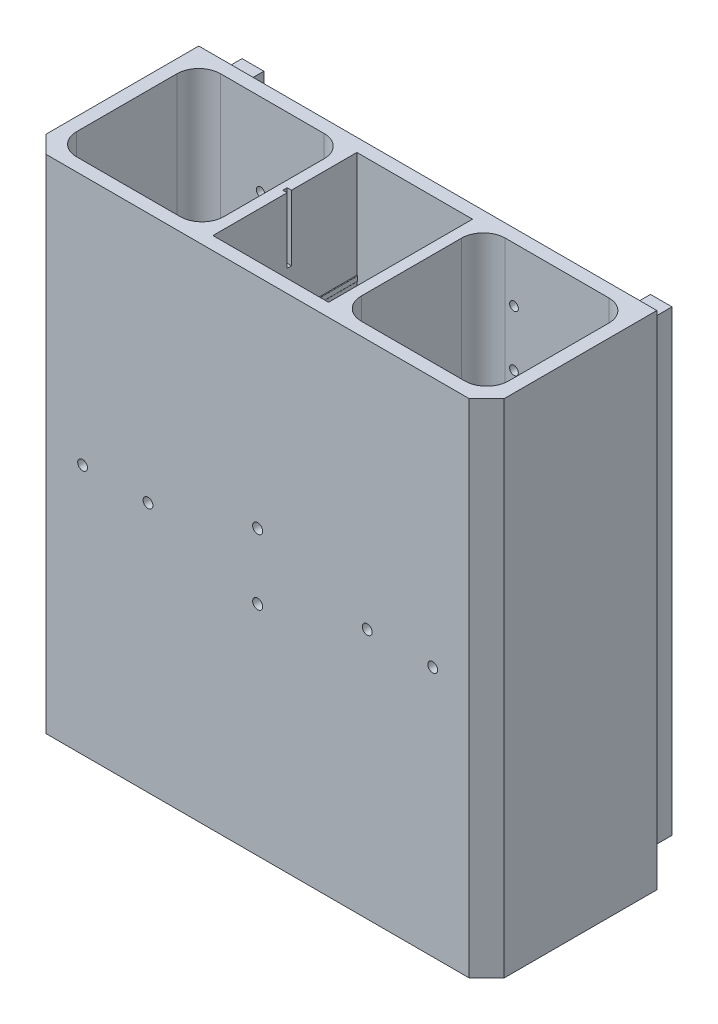
SolidWorks part; units mm, degrees
ref_plane "前视基准面" through (0, 0, 0) normal (0, 0, 1) x (1, 0, 0)
ref_plane "上视基准面" through (0, 0, 0) normal (0, 1, 0) x (1, 0, 0)
ref_plane "右视基准面" through (0, 0, 0) normal (1, 0, 0) x (0, 0, -1)
other "Configuration Table"
sketch "草图1" plane through (0, 0, 0) normal (0, 0, 1) x (1, 0, 0)
  line L1 (0, 0) -> (210, 0)
  line L2 (0, 0) -> (0, 230)
  line L3 (0, 230) -> (210, 230)
  line L4 (210, 0) -> (210, 230)
  line L5 (0, 0) -> (210, 230) construction
  line L6 (0, 230) -> (210, 0) construction
  line L7 (0, 230) -> (26, 230)
  line L8 (0, 230) -> (0, 0)
  line L9 (0, 0) -> (26, 0)
  point P4 (105, 115)
  point P8 (13, 115)
  dimension "D1" = 230
  dimension "D2" = 210
extrude "凸台-拉伸1" add sketch "草图1" along normal blind 6 contours L1 L4 L3 L2
sketch "草图2" plane through (0, 0, 0) normal (0, 0, -1) x (-1, 0, 0)
  line L0 (0, 230) -> (-210, 230) construction
  line L1 (0, 0) -> (-210, 0) construction
  line L2 (-210, 230) -> (-184, 230)
  line L3 (-210, 230) -> (-210, 0)
  line L4 (-210, 0) -> (-184, 0)
  line L5 (-184, 230) -> (-184, 0) construction
  line L6 (-210, 230) -> (-184, 0) construction
  line L7 (-210, 0) -> (-184, 230) construction
  line L9 (0, 230) -> (-20, 230)
  line L10 (0, 230) -> (0, 0)
  line L11 (0, 0) -> (-20, 0)
  line L13 (0, 230) -> (-20, 0) construction
  line L14 (0, 0) -> (-20, 230) construction
  line L15 (-201.925, 219.925) -> (-192.075, 219.925)
  line L16 (-201.925, 219.925) -> (-201.925, 10.075)
  line L17 (-201.925, 10.075) -> (-192.075, 10.075)
  line L18 (-192.075, 219.925) -> (-192.075, 10.075)
  line L19 (-201.925, 219.925) -> (-192.075, 10.075) construction
  line L20 (-201.925, 10.075) -> (-192.075, 219.925) construction
  line L21 (-14.85, 219.925) -> (-4.85, 219.925)
  line L22 (-14.85, 219.925) -> (-14.85, 10.075)
  line L23 (-14.85, 10.075) -> (-4.85, 10.075)
  line L24 (-4.85, 219.925) -> (-4.85, 10.075)
  line L25 (-14.85, 219.925) -> (-4.85, 10.075) construction
  line L26 (-14.85, 10.075) -> (-4.85, 219.925) construction
  point P6 (-197, 115)
  point P18 (-197, 115)
  point P23 (-9.85, 115)
  dimension "D1" = 26
  dimension "D2" = 20
  dimension "D3" = 209.85
  dimension "D4" = 9.85
  dimension "D5" = 13
  dimension "D6" = 115
  dimension "D7" = 209.85
  dimension "D8" = 115
  dimension "D9" = 9.85
  dimension "D10" = 10
extrude "凸台-拉伸3" add sketch "草图2" along normal blind 15 contours L18 L15 L16 L17 | L24 L21 L22 L23
sketch "草图3" plane through (0, 0, 0) normal (0, 0, -1) x (-1, 0, 0)
  line L0 (0, 0) -> (-210, 0) construction
  line L1 (-210, 230) -> (-184, 230)
  line L2 (-210, 230) -> (-210, 0)
  line L3 (-210, 0) -> (-184, 0)
  line L4 (-184, 230) -> (-184, 0)
  line L5 (-210, 230) -> (-184, 0) construction
  line L6 (-210, 0) -> (-184, 230) construction
  line L7 (-210, 115) -> (119.2636, 115) construction
  line L8 (0, 230) -> (-20, 230)
  line L9 (0, 230) -> (0, 0)
  line L10 (0, 0) -> (-20, 0)
  line L11 (-20, 230) -> (-20, 0)
  line L12 (0, 230) -> (-20, 0) construction
  line L13 (0, 0) -> (-20, 230) construction
  line L14 (-105, 230) -> (-105, 0) construction
  circle A0 centre (-169.6426, 192.25) radius 2
  circle A1 centre (-150.5, 205) radius 2
  circle A2 centre (-150.5, 179.5) radius 2
  circle A3 centre (-150.5, 50.5) radius 2
  circle A4 centre (-150.5, 25) radius 2
  circle A5 centre (-169.6426, 37.75) radius 2
  circle A6 centre (-34.3574, 192.25) radius 2
  circle A7 centre (-53.5, 205) radius 2
  circle A8 centre (-53.5, 179.5) radius 2
  circle A9 centre (-53.5, 50.5) radius 2
  circle A10 centre (-53.5, 25) radius 2
  circle A11 centre (-34.3574, 37.75) radius 2
  point P4 (-197, 115)
  point P12 (-10, 115)
  dimension "D8" = 4
  dimension "D9" = 4
  dimension "D10" = 4
  dimension "D12" = 4
  dimension "D13" = 4
  dimension "D14" = 4
  dimension "D1" = 26
  dimension "D2" = 20
  dimension "D3" = 25.5
  dimension "D4" = 23
  dimension "D5" = 23
  dimension "D6" = 33.5
  dimension "D7" = 33.5
  dimension "D11" = 90
  dimension "D15" = 25.5
  dimension "D16" = 23
  dimension "D17" = 23
  dimension "D18" = 33.5
  dimension "D19" = 33.5
  dimension "D20" = 90
extrude "切除-拉伸1" cut sketch "草图3" against normal blind 10 contours A10 | A11 | A9 | A6 | A8 | A7 | A1 | A2 | A0 | A4 | A3 | A5
chamfer "倒角1" [suppressed] distance 10 angle 45
sketch "草图5" [suppressed] plane through (0, 0, 0) normal (0, 0, -1) x (-1, 0, 0)
  line L0 (-172.5, 115) -> (-135, 115) construction
  line L1 (-10, 230) -> (-200, 230) construction
  line L2 (-210, 10) -> (-210, 220) construction
  line L5 (-210, 220) -> (-210, 0)
  line L8 (-75, 115) -> (-37.5, 115) construction
  line L9 (-210, 0) -> (-184, 220) construction
  line L10 (0, 10) -> (0, 220) construction
  circle A0 centre (-172.5, 115) radius 2.5
  circle A1 centre (-135, 115) radius 2.5
  circle A2 centre (-75, 115) radius 2.5
  circle A3 centre (-37.5, 115) radius 2.5
  point P12 (-197, 110)
  dimension "D3" = 5
  dimension "D4" = 5
  dimension "D8" = 5
  dimension "D9" = 5
  dimension "D1" = 37.5
  dimension "D2" = 115
  dimension "D5" = 75
  dimension "D6" = 26
  dimension "D7" = 37.5
  dimension "D10" = 115
  dimension "D11" = 75
extrude "切除-拉伸2" [suppressed] cut sketch "草图5" against normal blind 10 contours A0 | A1 | A3 | A2
sketch "草图6" plane through (0, 0, 6) normal (0, 0, 1) x (1, 0, 0)
  line L0 (105, 230) -> (105, 0) construction
  line L3 (0, 115) -> (210, 115) construction
  line L6 (86.25, 115) -> (123.75, 115) construction
  line L7 (105, 133.75) -> (105, 96.25) construction
  circle A2 centre (105, 133.75) radius 2.5
  circle A3 centre (105, 96.25) radius 2.5
  point P7 (105, 115)
  point P11 (105, 115)
  dimension "D1" = 37.5
  dimension "D2" = 5
  dimension "D3" = 5
extrude "切除-拉伸3" [suppressed] cut sketch "草图6" against normal blind 10
sketch "草图7" [suppressed] plane through (0, 0, 18) normal (0, 0, 1) x (1, 0, 0)
  line L0 (0, 0) -> (210, 0) construction
  line L1 (0, 230) -> (6, 230)
  line L2 (0, 230) -> (0, 0)
  line L3 (0, 0) -> (6, 0)
  line L4 (6, 230) -> (6, 0)
  line L5 (0, 230) -> (6, 0) construction
  line L6 (0, 0) -> (6, 230) construction
  point P4 (3, 115)
  dimension "D1" = 6
extrude "凸台-拉伸4" [suppressed] add sketch "草图7" along normal blind 55
sketch "草图8" [suppressed] plane through (0, 0, 18) normal (0, 0, 1) x (1, 0, 0)
  line L0 (0, 0) -> (210, 0) construction
  line L1 (210, 230) -> (200.2731, 230)
  line L2 (210, 230) -> (210, 0)
  line L3 (210, 0) -> (200.2731, 0)
  line L4 (200.2731, 230) -> (200.2731, 0)
  line L5 (210, 230) -> (200.2731, 0) construction
  line L6 (210, 0) -> (200.2731, 230) construction
  point P4 (205.1365, 115)
  dimension "D1" = 9.7269
sketch "草图17" plane through (0, 0, 6) normal (0, 0, 1) x (1, 0, 0)
  line L0 (0, 0) -> (210, 0) construction
  line L1 (0, 230) -> (6, 230)
  line L2 (0, 230) -> (0, 0)
  line L3 (0, 0) -> (6, 0)
  line L4 (6, 230) -> (6, 0)
  line L5 (0, 230) -> (6, 0) construction
  line L6 (0, 0) -> (6, 230) construction
  line L8 (210, 230) -> (204, 230)
  line L9 (210, 230) -> (210, 0)
  line L10 (210, 0) -> (204, 0)
  line L11 (204, 230) -> (204, 0)
  line L12 (210, 230) -> (204, 0) construction
  line L13 (210, 0) -> (204, 230) construction
  point P4 (3, 115)
  point P12 (207, 115)
  dimension "D1" = 6
  dimension "D2" = 6
extrude "凸台-拉伸9" add sketch "草图17" along normal blind 66
ref_plane "基准面2" through (0, 0, 72) normal (0, 0, 1) x (1, 0, 0)
sketch "草图18" plane through (0, 0, 72) normal (0, 0, 1) x (1, 0, 0)
  line L0 (210, 230) -> (204, 230) construction
  line L1 (210, 0) -> (210, 230) construction
  line L2 (204, 0) -> (210, 0) construction
  line L3 (6, 0) -> (204, 0) construction
  line L4 (0, 0) -> (6, 0) construction
  line L5 (0, 230) -> (0, 0) construction
  line L6 (6, 230) -> (0, 230) construction
  line L7 (6, 230) -> (204, 230) construction
  line L8 (210, 230) -> (204, 230)
  line L9 (210, 0) -> (210, 230)
  line L10 (204, 0) -> (210, 0)
  line L11 (6, 0) -> (204, 0)
  line L12 (0, 0) -> (6, 0)
  line L13 (0, 230) -> (0, 0)
  line L14 (6, 230) -> (0, 230)
  line L15 (6, 230) -> (204, 230)
extrude "凸台-拉伸10" add sketch "草图18" along normal blind 6
chamfer "倒角3" distance 8 angle 45 2 edges at (0, 115, 78) (210, 115, 78)
sketch "草图19" plane through (0, 0, 72) normal (0, 0, -1) x (-1, 0, 0)
  line L0 (-105, 230) -> (-105, 0) construction
  line L2 (-131.5, 230) -> (-136.5, 230)
  line L3 (0, 230) -> (-210, 230) construction
  line L4 (0, 0) -> (-210, 0) construction
  line L5 (-131.5, 230) -> (-131.5, 0)
  line L6 (-131.5, 230) -> (-78.5, 230)
  line L7 (-131.5, 230) -> (-131.5, 0)
  line L8 (-131.5, 0) -> (-78.5, 0)
  line L9 (-78.5, 230) -> (-78.5, 0)
  line L10 (-131.5, 230) -> (-78.5, 0) construction
  line L11 (-131.5, 0) -> (-78.5, 230) construction
  line L12 (-131.5, 0) -> (-136.5, 0)
  line L13 (-136.5, 230) -> (-136.5, 0)
  line L14 (-131.5, 230) -> (-136.5, 0) construction
  line L15 (-131.5, 0) -> (-136.5, 230) construction
  line L16 (-78.5, 230) -> (-73.5, 230)
  line L17 (-78.5, 230) -> (-78.5, 0)
  line L18 (-78.5, 0) -> (-73.5, 0)
  line L19 (-73.5, 230) -> (-73.5, 0)
  line L20 (-78.5, 230) -> (-73.5, 0) construction
  line L21 (-78.5, 0) -> (-73.5, 230) construction
  point P10 (-105, 115)
  point P13 (-134, 115)
  point P16 (-76, 115)
  dimension "D1" = 53
  dimension "D2" = 0
  dimension "D3" = 5
  dimension "D4" = 5
extrude "凸台-拉伸11" add sketch "草图19" along normal blind 66 contours L19 L7 L9 L4 | L7 L13 L4 L5
fillet "圆角4" radius 10 8 edges at (136.5, 115, 72) (136.5, 115, 6) (204, 115, 6) (204, 115, 72) (73.5, 115, 6) (73.5, 115, 72) (6, 115, 6) (6, 115, 72)
sketch "草图21" plane through (0, 0, 72) normal (0, 0, 1) x (1, 0, 0)
  line L0 (8, 115) -> (202, 115) construction
  line L1 (8, 230) -> (8, 0) construction
  line L2 (202, 0) -> (202, 230) construction
  line L3 (105, 230) -> (105, 0) construction
  line L4 (202, 230) -> (8, 230) construction
  line L5 (8, 0) -> (202, 0) construction
  line L6 (105, 130) -> (105, 100) construction
  circle A0 centre (105, 130) radius 2.3
  circle A1 centre (105, 100) radius 2.3
  point P14 (105, 115)
  dimension "D3" = 4.6
  dimension "D4" = 4.6
  dimension "D1" = 0
  dimension "D2" = 30
extrude "切除-拉伸9" cut sketch "草图21" along normal blind 6 contours A1 | A0
sketch "草图23" plane through (78.5, 0, 0) normal (1, 0, 0) x (0, 0, -1)
  line L0 (-6, 80) -> (-70, 80)
  line L1 (-6, 230) -> (-70, 230) construction
  line L2 (-6, 230) -> (-6, 0) construction
  line L3 (-6, 0) -> (-70, 0) construction
  line L4 (-70, 230) -> (-70, 0) construction
  line L5 (-6, 230) -> (-70, 0) construction
  line L6 (-6, 0) -> (-70, 230) construction
  line L7 (-6, 230) -> (-70, 230)
  line L8 (-6, 230) -> (-6, 40)
  line L9 (-6, 40) -> (-70, 40)
  line L10 (-70, 230) -> (-70, 40)
  line L11 (-6, 230) -> (-70, 40) construction
  line L12 (-6, 40) -> (-70, 230) construction
  point P4 (-38, 115)
  point P9 (-38, 135)
  dimension "D1" = 190
  dimension "D2" = 40
sketch "草图24" plane through (0, 0, 6) normal (0, 0, 1) x (1, 0, 0)
  line L0 (78.5, 80.5) -> (78.5, 79.5) construction
  line L1 (78.5, 230) -> (78.5, 40) construction
  line L2 (80, 80.5) -> (80, 79.5)
  line L4 (78.5, 82) -> (78.5, 78)
  arc A0 (80, 80.5) -> (78.5, 82) centre (78.5, 80.5) ccw
  arc A1 (78.5, 78) -> (80, 79.5) centre (78.5, 79.5) ccw
  point P0 (78.5, 80)
  point P6 (78.5, 80)
  dimension "D3" = 1.5
  dimension "D4" = 1.5
  dimension "D1" = 0
  dimension "D2" = 1
extrude "凸台-拉伸12" [suppressed] add sketch "草图24" along normal blind 66
ref_plane "基准面3" through (105, 0, 0) normal (-1, 0, 0) x (0, 0, 1)
mirror "镜向1" [suppressed] about plane through (105, 0, 0) normal (-1, 0, 0)
sketch "草图25" plane through (0, 0, 72) normal (0, 0, -1) x (-1, 0, 0)
  line L8 (-131.5, 230) -> (-131.5, 0)
  line L11 (-131.5, 0) -> (-78.5, 0)
  line L12 (-78.5, 0) -> (-78.5, 230)
  line L15 (-78.5, 230) -> (-131.5, 230)
  line L16 (-131.5, 230) -> (-131.5, 0)
  line L19 (-131.5, 0) -> (-78.5, 0)
  line L20 (-78.5, 0) -> (-78.5, 230)
  line L23 (-78.5, 230) -> (-131.5, 230)
  dimension "D1" = 0
sketch "草图26" plane through (0, 0, 72) normal (0, 0, -1) x (-1, 0, 0)
  line L0 (-131.5, 181) -> (-131.5, 179) construction
  line L1 (-131.5, 230) -> (-131.5, 0) construction
  line L2 (-131.26, 181) -> (-131.26, 179)
  line L3 (-131.74, 181) -> (-131.74, 179)
  line L4 (-78.5, 230) -> (-131.5, 230) construction
  line L5 (-131.5, 230) -> (-131.5, 0) construction
  line L6 (-78.5, 230) -> (-131.5, 230) construction
  line L7 (-131.5, 22.5) -> (-131.5, 20.5) construction
  line L8 (-131.26, 22.5) -> (-131.26, 20.5)
  line L9 (-131.74, 22.5) -> (-131.74, 20.5)
  arc A0 (-131.26, 181) -> (-131.74, 181) centre (-131.5, 181) ccw
  arc A1 (-131.74, 179) -> (-131.26, 179) centre (-131.5, 179) ccw
  arc A2 (-131.26, 22.5) -> (-131.74, 22.5) centre (-131.5, 22.5) ccw
  arc A3 (-131.74, 20.5) -> (-131.26, 20.5) centre (-131.5, 20.5) ccw
  point P4 (-131.5, 180)
  point P14 (-131.5, 21.5)
  dimension "D1" = 0.24
  dimension "D2" = 2
  dimension "D3" = 50
  dimension "D4" = 2
extrude "凸台-拉伸13" add sketch "草图26" along normal blind 66
mirror "镜向2" about plane through (105, 0, 0) normal (-1, 0, 0) of "凸台-拉伸13"
sketch "草图28" plane through (0, 0, 72) normal (0, 0, -1) x (-1, 0, 0)
  line L0 (-78.5, 230) -> (-131.5, 230) construction
  line L1 (-78.5, 230) -> (-131.5, 230) construction
  line L2 (-131.5, 230) -> (-131.5, 0) construction
  line L3 (-131.5, 11.46) -> (-78.5, 11.46)
  line L4 (-131.5, 11.46) -> (-131.5, 8.46)
  line L5 (-131.5, 8.46) -> (-78.5, 8.46)
  line L6 (-78.5, 11.46) -> (-78.5, 8.46)
  line L7 (-131.5, 11.46) -> (-78.5, 8.46) construction
  line L8 (-131.5, 8.46) -> (-78.5, 11.46) construction
  line L9 (-78.5, 230) -> (-78.5, 0) construction
  point P6 (-105, 9.96)
  point P11 (-78.5, 20.2624)
  dimension "D1" = 218.54
  dimension "D2" = 3
extrude "凸台-拉伸14" add sketch "草图28" along normal blind 66
sketch "草图30" plane through (0, 230, 0) normal (0, 1, 0) x (1, 0, 0)
  line L0 (78.5, -6) -> (131.5, -6) construction
  line L1 (78.5, -6) -> (131.5, -6) construction
  line L2 (78.5, -6) -> (78.5, -70) construction
  line L3 (78.5, -36) -> (76.5, -36)
  line L4 (78.5, -36) -> (78.5, -38)
  line L5 (78.5, -38) -> (76.5, -38)
  line L6 (76.5, -36) -> (76.5, -38)
  line L7 (78.5, -36) -> (76.5, -38) construction
  line L8 (78.5, -38) -> (76.5, -36) construction
  point P6 (77.5, -37)
  dimension "D1" = 2
  dimension "D2" = 30
  dimension "D3" = 2
extrude "切除-拉伸10" cut sketch "草图30" against normal blind 30
sketch "草图31" plane through (0, 8.46, 0) normal (0, -1, 0) x (1, 0, 0)
  line L0 (105, 72) -> (105, 6) construction
  line L1 (105, 15.7) -> (117.5, 15.7) construction
  line L2 (98.5, 22.2) -> (111.5, 22.2)
  line L3 (98.5, 22.2) -> (98.5, 9.2)
  line L4 (131.5, 72) -> (78.5, 72)
  line L5 (78.5, 72) -> (78.5, 6)
  line L6 (78.5, 6) -> (131.5, 6)
  line L7 (131.5, 6) -> (131.5, 72)
  line L8 (131.5, 72) -> (78.5, 72) construction
  line L9 (78.5, 72) -> (78.5, 6) construction
  line L10 (78.5, 6) -> (131.5, 6) construction
  line L11 (131.5, 6) -> (131.5, 72) construction
  line L12 (98.5, 9.2) -> (111.5, 9.2)
  line L13 (111.5, 22.2) -> (111.5, 9.2)
  line L14 (98.5, 22.2) -> (111.5, 9.2) construction
  line L15 (98.5, 9.2) -> (111.5, 22.2) construction
  circle A0 centre (92.7, 15.7) radius 1.25
  circle A1 centre (117.3, 15.7) radius 1.25
  point P10 (105, 15.7)
  point P17 (0, 0)
  dimension "D8" = 2.5
  dimension "D9" = 2.5
  dimension "D2" = 13
  dimension "D3" = 13
  dimension "D4" = 12.3
  dimension "D5" = 12.3
  dimension "D6" = 3.2
  dimension "D7" = 0
  dimension "D1" = 0
extrude "切除-拉伸11" cut sketch "草图31" against normal through all
sketch "草图32" plane through (0, 0, 6) normal (0, 0, 1) x (1, 0, 0)
  line L0 (131.5, 8.46) -> (78.5, 8.46) construction
  line L1 (119.5, 8.46) -> (131.5, 8.46)
  line L2 (119.5, 8.46) -> (119.5, -1.54)
  line L3 (119.5, -1.54) -> (131.5, -1.54)
  line L4 (131.5, 8.46) -> (131.5, -1.54)
  line L5 (119.5, 8.46) -> (131.5, -1.54) construction
  line L6 (119.5, -1.54) -> (131.5, 8.46) construction
  line L7 (131.5, 8.46) -> (78.5, 8.46) construction
  line L8 (131.5, 8.46) -> (131.5, 0) construction
  line L9 (131.5, 8.46) -> (131.5, 0) construction
  line L10 (78.5, 0) -> (131.5, 0) construction
  line L11 (78.5, 0) -> (131.5, 0) construction
  point P4 (125.5, 3.46)
  dimension "D1" = 10
  dimension "D2" = 0
  dimension "D3" = 0
  dimension "D4" = 12
extrude "切除-拉伸12" cut sketch "草图32" against normal through all
sketch "草图33" plane through (131.5, 0, 0) normal (-1, 0, 0) x (0, 0, 1)
  line L0 (0, 8.46) -> (72, 8.46) construction
  line L1 (30, 8.46) -> (50, 8.46)
  line L2 (30, 8.46) -> (30, 0)
  line L3 (30, 0) -> (50, 0)
  line L4 (50, 8.46) -> (50, 0)
  line L5 (30, 8.46) -> (50, 0) construction
  line L6 (30, 0) -> (50, 8.46) construction
  line L7 (0, 0) -> (72, 0) construction
  line L8 (0, 0) -> (0, 8.46) construction
  point P4 (40, 4.23)
  point P9 (30, 4.23)
  dimension "D1" = 20
  dimension "D2" = 30
extrude "切除-拉伸13" cut sketch "草图33" against normal up to next
sketch "草图34" plane through (0, 0, 72) normal (0, 0, -1) x (-1, 0, 0)
  line L0 (-170.25, 230) -> (-170.25, 0) construction
  line L1 (-194, 115) -> (-146.5, 115) construction
  line L2 (-185.25, 115) -> (-155.25, 115)
  line L4 (-194, 0) -> (-146.5, 0)
  line L5 (-146.5, 0) -> (-146.5, 230)
  line L6 (-146.5, 230) -> (-194, 230)
  line L7 (-194, 230) -> (-194, 0)
  line L8 (-194, 0) -> (-146.5, 0) construction
  line L9 (-146.5, 0) -> (-146.5, 230) construction
  line L10 (-146.5, 230) -> (-194, 230) construction
  line L11 (-194, 230) -> (-194, 0) construction
  circle A0 centre (-185.25, 115) radius 2.25
  circle A1 centre (-155.25, 115) radius 2.25
  point P12 (-170.25, 115)
  dimension "D2" = 4.5
  dimension "D3" = 4.5
  dimension "D4" = 30
  dimension "D1" = 0
extrude "切除-拉伸14" cut sketch "草图34" against normal blind 30 contours A0 | A1
sketch "草图36" plane through (0, 0, 72) normal (0, 0, -1) x (-1, 0, 0)
  line L0 (-39.75, 230) -> (-39.75, 0) construction
  line L1 (-63.5, 115) -> (-16, 115) construction
  line L2 (-54.75, 115) -> (-24.75, 115)
  line L4 (-16, 230) -> (-63.5, 230)
  line L5 (-63.5, 230) -> (-63.5, 0)
  line L6 (-63.5, 0) -> (-16, 0)
  line L7 (-16, 0) -> (-16, 230)
  line L8 (-16, 230) -> (-63.5, 230) construction
  line L9 (-63.5, 230) -> (-63.5, 0) construction
  line L10 (-63.5, 0) -> (-16, 0) construction
  line L11 (-16, 0) -> (-16, 230) construction
  circle A0 centre (-54.75, 115) radius 2.25
  circle A1 centre (-24.75, 115) radius 2.25
  point P12 (-39.75, 115)
  dimension "D2" = 4.5
  dimension "D3" = 4.5
  dimension "D4" = 30
  dimension "D1" = 0
extrude "切除-拉伸15" cut sketch "草图36" against normal blind 30
